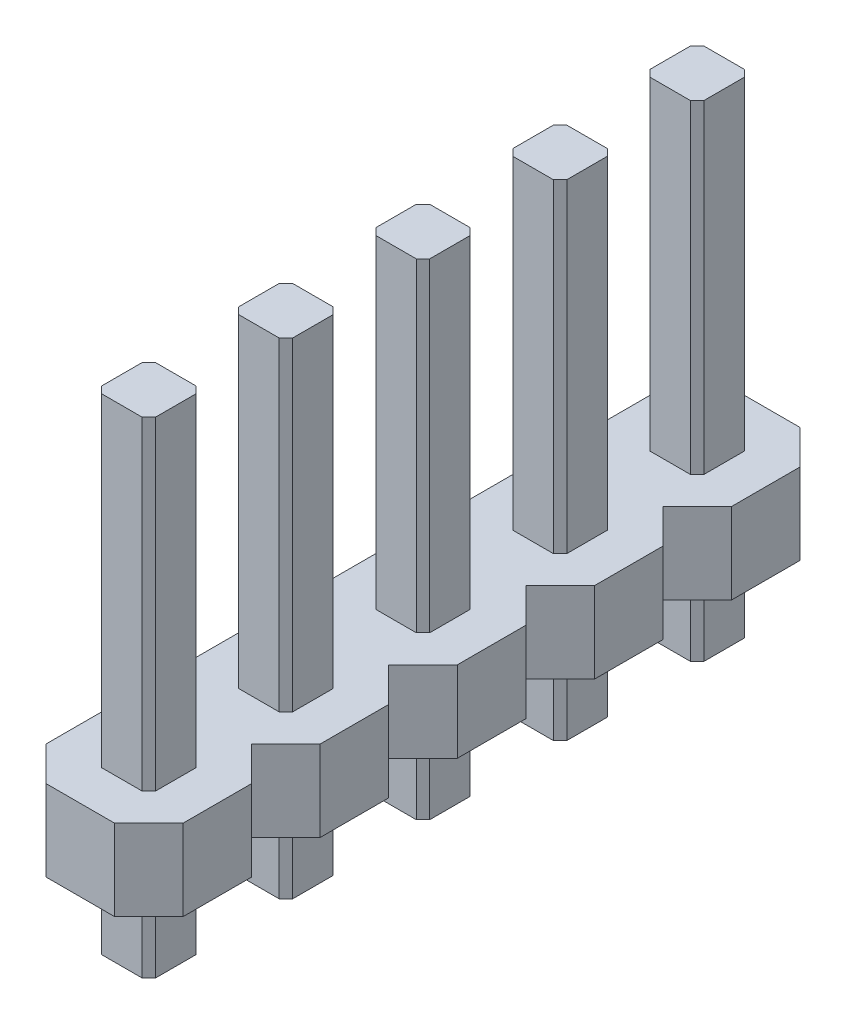
SolidWorks part; units mm, degrees
ref_plane "Plan de face" through (0, 0, 0) normal (0, 0, 1) x (1, 0, 0)
ref_plane "Plan de dessus" through (0, 0, 0) normal (0, 1, 0) x (1, 0, 0)
ref_plane "Plan de droite" through (0, 0, 0) normal (1, 0, 0) x (0, 0, -1)
sketch "Sketch1" plane through (0, 0, 0) normal (0, 1, 0) x (1, 0, 0)
  line L0 (-0.635, 1.27) -> (0.635, 1.27)
  line L1 (0.635, 1.27) -> (1.27, 0.635)
  line L2 (1.27, 0.635) -> (1.27, -0.635)
  line L3 (1.27, -0.635) -> (0.635, -1.27)
  line L4 (-0.635, 1.27) -> (-1.27, 0.635)
  line L5 (-1.27, 0.635) -> (-1.27, -0.635)
  line L6 (-1.27, -0.635) -> (-0.635, -1.27)
  line L7 (0.635, -1.27) -> (1.27, -1.905)
  line L8 (1.27, -1.905) -> (1.27, -3.175)
  line L9 (1.27, -3.175) -> (0.635, -3.81)
  line L10 (-0.635, -1.27) -> (-1.27, -1.905)
  line L11 (-1.27, -1.905) -> (-1.27, -3.175)
  line L12 (-1.27, -3.175) -> (-0.635, -3.81)
  line L13 (0.635, -3.81) -> (1.27, -4.445)
  line L14 (1.27, -4.445) -> (1.27, -5.715)
  line L15 (1.27, -5.715) -> (0.635, -6.35)
  line L16 (-0.635, -3.81) -> (-1.27, -4.445)
  line L17 (-1.27, -4.445) -> (-1.27, -5.715)
  line L18 (-1.27, -5.715) -> (-0.635, -6.35)
  line L19 (0.635, -6.35) -> (1.27, -6.985)
  line L20 (1.27, -6.985) -> (1.27, -8.255)
  line L21 (1.27, -8.255) -> (0.635, -8.89)
  line L22 (-0.635, -6.35) -> (-1.27, -6.985)
  line L23 (-1.27, -6.985) -> (-1.27, -8.255)
  line L24 (-1.27, -8.255) -> (-0.635, -8.89)
  line L25 (0.635, -8.89) -> (1.27, -9.525)
  line L26 (1.27, -9.525) -> (1.27, -10.795)
  line L27 (1.27, -10.795) -> (0.635, -11.43)
  line L28 (-0.635, -8.89) -> (-1.27, -9.525)
  line L29 (-1.27, -9.525) -> (-1.27, -10.795)
  line L30 (-1.27, -10.795) -> (-0.635, -11.43)
  line L50 (-0.635, -1.27) -> (0.635, -1.27) construction
  line L51 (0, 1.27) -> (0, -1.27) construction
  line L52 (-0.635, -11.43) -> (0.635, -11.43)
  point P0 (0, 0)
  point P1 (0, 0)
  point P54 (0, 0)
extrude "Boss-Extrude1" add sketch "Sketch1" along normal blind 1.5
sketch "Sketch2" plane through (0, 1.5, 0) normal (0, 1, 0) x (1, 0, 0)
  line L0 (0.5, 0.375) -> (0.375, 0.5)
  line L1 (0.375, 0.5) -> (-0.375, 0.5)
  line L2 (0.5, 0.375) -> (0.5, -0.375)
  line L3 (0.375, -0.5) -> (-0.375, -0.5)
  line L4 (-0.5, 0.375) -> (-0.5, -0.375)
  line L5 (0.5, 0.5) -> (-0.5, -0.5) construction
  line L6 (0.5, -0.5) -> (-0.5, 0.5) construction
  line L7 (-0.375, 0.5) -> (-0.5, 0.375)
  line L8 (-0.375, -0.5) -> (-0.5, -0.375)
  line L9 (0.5, -0.375) -> (0.375, -0.5)
  line L10 (0.5, -2.165) -> (0.375, -2.04)
  line L11 (0.375, -2.04) -> (-0.375, -2.04)
  line L12 (0.5, -2.165) -> (0.5, -2.915)
  line L13 (0.375, -3.04) -> (-0.375, -3.04)
  line L14 (-0.5, -2.165) -> (-0.5, -2.915)
  line L15 (-0.375, -2.04) -> (-0.5, -2.165)
  line L16 (-0.375, -3.04) -> (-0.5, -2.915)
  line L17 (0.5, -2.915) -> (0.375, -3.04)
  line L18 (0.5, -2.04) -> (-0.5, -3.04) construction
  line L19 (0.5, -3.04) -> (-0.5, -2.04) construction
  line L20 (0.5, -4.705) -> (0.375, -4.58)
  line L21 (0.375, -4.58) -> (-0.375, -4.58)
  line L22 (0.5, -4.705) -> (0.5, -5.455)
  line L23 (0.375, -5.58) -> (-0.375, -5.58)
  line L24 (-0.5, -4.705) -> (-0.5, -5.455)
  line L25 (-0.375, -4.58) -> (-0.5, -4.705)
  line L26 (-0.375, -5.58) -> (-0.5, -5.455)
  line L27 (0.5, -5.455) -> (0.375, -5.58)
  line L28 (0.5, -4.58) -> (-0.5, -5.58) construction
  line L29 (0.5, -5.58) -> (-0.5, -4.58) construction
  line L30 (0.5, -7.245) -> (0.375, -7.12)
  line L31 (0.375, -7.12) -> (-0.375, -7.12)
  line L32 (0.5, -7.245) -> (0.5, -7.995)
  line L33 (0.375, -8.12) -> (-0.375, -8.12)
  line L34 (-0.5, -7.245) -> (-0.5, -7.995)
  line L35 (-0.375, -7.12) -> (-0.5, -7.245)
  line L36 (-0.375, -8.12) -> (-0.5, -7.995)
  line L37 (0.5, -7.995) -> (0.375, -8.12)
  line L38 (0.5, -7.12) -> (-0.5, -8.12) construction
  line L39 (0.5, -8.12) -> (-0.5, -7.12) construction
  line L40 (0.5, -9.785) -> (0.375, -9.66)
  line L41 (0.375, -9.66) -> (-0.375, -9.66)
  line L42 (0.5, -9.785) -> (0.5, -10.535)
  line L43 (0.375, -10.66) -> (-0.375, -10.66)
  line L44 (-0.5, -9.785) -> (-0.5, -10.535)
  line L45 (-0.375, -9.66) -> (-0.5, -9.785)
  line L46 (-0.375, -10.66) -> (-0.5, -10.535)
  line L47 (0.5, -10.535) -> (0.375, -10.66)
  line L48 (0.5, -9.66) -> (-0.5, -10.66) construction
  line L49 (0.5, -10.66) -> (-0.5, -9.66) construction
  point P0 (0, 0)
  point P15 (0, -2.54)
  point P28 (0, -5.08)
  point P41 (0, -7.62)
  point P54 (0, -10.16)
  dimension "D1" = 1
  dimension "D2" = 1
  dimension "D3" = 5
extrude "Boss-Extrude2" add sketch "Sketch2" along normal blind 6 and the other way blind 3
